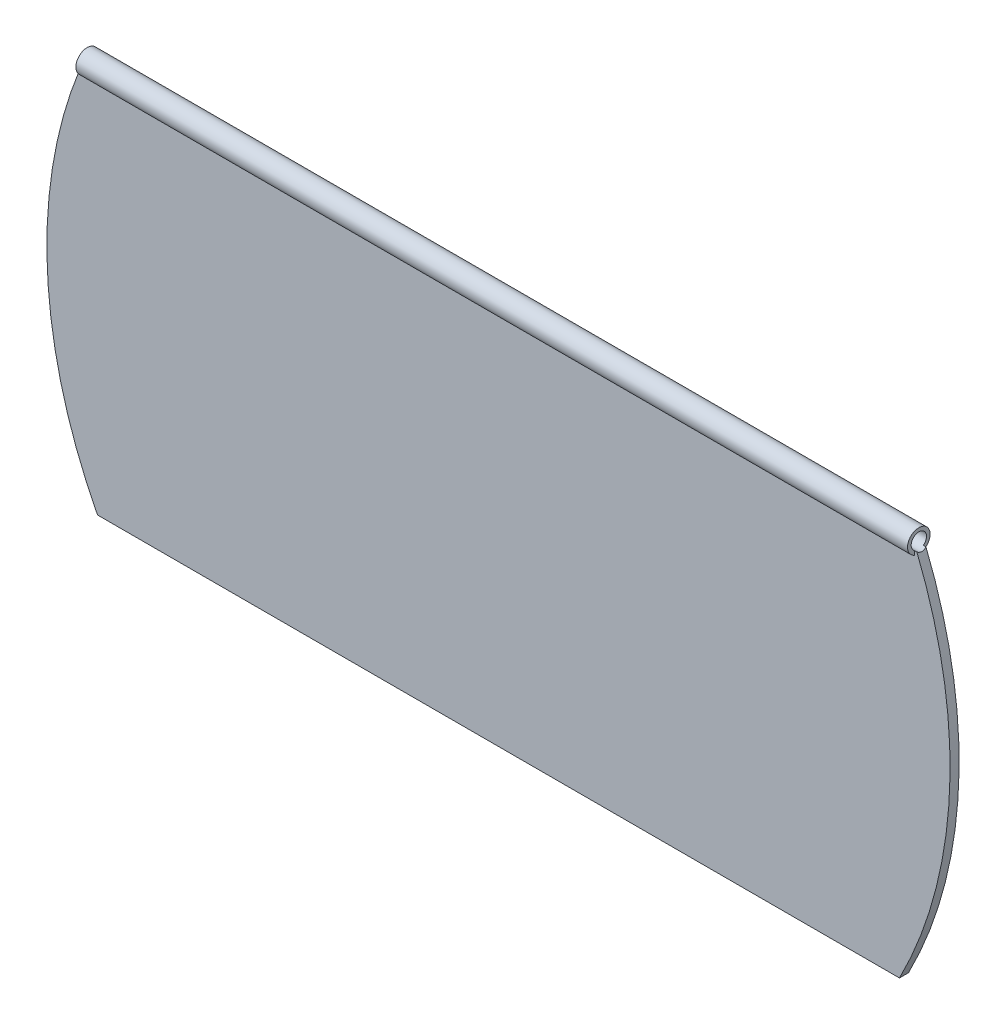
SolidWorks part; units mm, degrees
ref_plane "前视基准面" through (0, 0, 0) normal (0, 0, 1) x (1, 0, 0)
ref_plane "上视基准面" through (0, 0, 0) normal (0, 1, 0) x (1, 0, 0)
ref_plane "右视基准面" through (0, 0, 0) normal (1, 0, 0) x (0, 0, -1)
sketch "草图1" plane through (0, 0, 0) normal (0, 0, 1) x (1, 0, 0)
  arc A0 (-203, 0) -> (203, 0) centre (0, 0) ccw
  arc A1 (-210, 0) -> (210, 0) centre (0, 0) ccw
  arc A2 (-203, 0) -> (203, 0) centre (0, 0) ccw
  circle A3 centre (0, 0) radius 210
  circle A4 centre (0, 0) radius 203
  point P12 (0, 0)
extrude "凸台-拉伸2" add sketch "草图1" along normal blind 174
sketch "草图2" plane through (0, 0, 174) normal (0, 0, 1) x (1, 0, 0)
  line L0 (-173.7354, -102) -> (-170.7354, -102)
  line L1 (-170.7354, -102) -> (-170.7354, -105)
  line L2 (-170.7354, -105) -> (-173.7354, -105)
  line L3 (173.7354, -102) -> (170.7354, -102)
  line L4 (-173.7354, -102) -> (-175.5135, -102)
  line L6 (173.7354, -102) -> (175.5135, -102)
  line L7 (173.7354, -105) -> (170.7354, -105)
  line L8 (170.7354, -105) -> (170.7354, -102)
  circle A0 centre (0, 0) radius 203 construction
  arc A1 (0, -203) -> (-173.7354, -105) centre (0, 0) ccw
  circle M4 centre (0, 0) radius 203
extrude "凸台-拉伸4" add sketch "草图2" against normal up to surface (174 mm away) contours L0 L4 L2 L1 M4 | L8 L7 L6 L3 M4 up to face at (203, 0, 0)
sketch "草图3" plane through (0, 0, 174) normal (0, 0, 1) x (1, 0, 0)
  line L0 (-170.7354, -102) -> (238.3336, -102)
  line L1 (238.3336, -102) -> (254.3342, 272.2925)
  line L2 (254.3342, 272.2925) -> (-334.5694, 221.8511)
  line L3 (-170.7354, -102) -> (-306.8306, -102)
  line L4 (-306.8306, -102) -> (-334.5694, 221.8511)
extrude "切除-拉伸1" cut sketch "草图3" against normal blind 654
ref_plane "基准面1" through (0, -209.75, 0) normal (0, 1, 0) x (1, 0, 0)
sketch "草图5" plane through (0, 0, 174) normal (0, 0, 1) x (1, 0, 0)
  line L0 (0, -209.75) -> (120, -209.75)
  line L1 (95.7, -209.75) -> (-95.7, -209.75) construction
  line L2 (120, -209.75) -> (120, -172.0322)
  line L3 (0, -209.75) -> (-120, -209.75)
  line L4 (-120, -209.75) -> (-120, -172.0322)
  arc A0 (-120, -172.0322) -> (120, -172.0322) centre (0, 0) ccw
  arc M3 (-183.5647, -102) -> (183.5647, -102) centre (0, 0) ccw
extrude "凸台-拉伸5" add sketch "草图5" against normal up to surface (174 mm away) contours L4 L3 M3 | L0 L2 M3 up to face at (0, -129.25, 0)
sketch "草图6" plane through (0, 0, 174) normal (0, 0, 1) x (1, 0, 0)
  line L0 (-175.5135, -102) -> (-166.1957, -102)
  line L1 (175.5135, -102) -> (166.1957, -102)
  arc A0 (-166.1957, -102) -> (166.1957, -102) centre (0, 0) ccw
  arc A1 (-175.5135, -102) -> (175.5135, -102) centre (0, 0) ccw
extrude "凸台-拉伸6" add sketch "草图6" against normal up to surface (174 mm away) up to face at (0, -151.228, 0)
sketch "草图7" plane through (0, 0, 174) normal (0, 0, 1) x (1, 0, 0)
  line L0 (-166.9331, -92) -> (-166.9331, -95)
  line L1 (171.9331, -92) -> (166.9331, -92)
  line L2 (-171.9331, -92) -> (-166.9331, -92)
  line L3 (-188.4969, -92) -> (-171.9331, -92)
  line L4 (171.9331, -92) -> (188.4969, -92)
  line L5 (-166.9331, -95) -> (-170.2939, -95)
  line L6 (166.9331, -92) -> (166.9331, -95)
  line L7 (166.9331, -95) -> (170.2939, -95)
  arc A1 (-188.4969, -92) -> (188.4969, -92) centre (0, 0) ccw
  arc A2 (-170.2939, -95) -> (170.2939, -95) centre (0, 0) ccw
extrude "凸台-拉伸7" add sketch "草图7" against normal up to surface (174 mm away) up to face at (0, -169.2192, 0)
sketch "草图8" plane through (0, 0, 0) normal (0, 0, -1) x (-1, 0, 0)
  line L0 (166.9331, -92) -> (163.9331, -92)
  line L1 (163.9331, -92) -> (163.9331, -99)
  line L2 (163.9331, -99) -> (168, -99)
  line L3 (166.9331, -92) -> (166.9331, -95)
  line L4 (166.9331, -95) -> (170.2939, -95)
  line L6 (-166.9331, -95) -> (-170.2939, -95)
  line L7 (-166.9331, -92) -> (-166.9331, -95)
  line L8 (-163.9331, -99) -> (-168, -99)
  line L9 (-163.9331, -92) -> (-163.9331, -99)
  line L10 (-166.9331, -92) -> (-163.9331, -92)
  arc A0 (-170.2939, -95) -> (170.2939, -95) centre (0, 0) ccw construction
  arc A1 (168, -99) -> (170.2939, -95) centre (0, 0) ccw
  arc A2 (-168, -99) -> (-170.2939, -95) centre (0, 0) cw
extrude "凸台-拉伸8" add sketch "草图8" against normal up to surface (174 mm away) up to face at (0, -135.959, 174)
sketch "草图9" plane through (0, 0, 174) normal (0, 0, 1) x (1, 0, 0)
  line L0 (0, 0) -> (0, -337.2155)
  line L3 (-50, -195) -> (-50, -209.75)
  line L4 (-10.2439, -209.75) -> (-120, -209.75) construction
  line L5 (-50, -209.75) -> (50, -209.75)
  line L6 (10.2439, -209.75) -> (120, -209.75) construction
  line L7 (50, -209.75) -> (50, -195)
  line L8 (-50, -195) -> (-50, -182.2253)
  line L9 (-50, -182.2253) -> (50, -182.2253)
  line L10 (50, -182.2253) -> (50, -195)
  arc M4 (168, -99) -> (-168, -99) centre (0, 0) cw
  line M12 (-120, -209.75) -> (-10.2439, -209.75)
  line M14 (10.2439, -209.75) -> (120, -209.75)
extrude "切除-拉伸2" cut sketch "草图9" against normal blind 654 contours L9 L8 L0 M4 | L8 L3 L5 L0 M12 M4 | L10 L0 L5 L7 M4 M14 | L10 L9 L0 M4
sketch "草图10" plane through (0, -209.75, 0) normal (0, 1, 0) x (1, 0, 0)
  line L1 (-10.2439, 0) -> (10.2439, 0)
  line L2 (-10.2439, 0) -> (-10.2439, -174)
  line L3 (-10.2439, -174) -> (10.2439, -174)
  line L4 (10.2439, 0) -> (10.2439, -174)
extrude "切除-拉伸3" cut sketch "草图10" against normal mid plane 654
sketch "草图11" plane through (0, 0, 0) normal (0, 0, -1) x (-1, 0, 0)
  line L1 (18.7676, -16.6345) -> (254.4053, -16.6345)
  line L2 (18.7676, -16.6345) -> (18.7676, -265.8266)
  line L3 (18.7676, -265.8266) -> (254.4053, -265.8266)
  line L4 (254.4053, -16.6345) -> (254.4053, -265.8266)
extrude "切除-拉伸4" cut sketch "草图11" against normal blind 238
ref_plane "基准面2" through (0, 0, 209.75) normal (0, 0, 1) x (1, 0, 0)
sketch "草图14" plane through (0, 0, 209.75) normal (0, 0, 1) x (1, 0, 0)
  line L0 (188.4969, -92) -> (183.1966, -92)
  line L1 (0, 210) -> (0, 205)
  line L2 (183.1966, -92) -> (188.775, -92)
  arc A0 (183.1966, -92) -> (0, 205) centre (0, 0) ccw
  arc A1 (188.775, -92) -> (0, 210) centre (0, 0) ccw
extrude "凸台-拉伸10" add sketch "草图14" along normal blind 174 separate body contours A0 L1 A1 L2
sketch "草图17" plane through (0, -92, 0) normal (0, 1, 0) x (1, 0, 0)
  line L1 (-19.1853, 5.1617) -> (266.9134, 5.1617)
  line L2 (-19.1853, 5.1617) -> (-19.1853, -186.717)
  line L3 (-19.1853, -186.717) -> (266.9134, -186.717)
  line L4 (266.9134, 5.1617) -> (266.9134, -186.717)
extrude "切除-拉伸5" cut sketch "草图17" against normal blind 322
sketch "草图18" plane through (0, 0, 383.75) normal (0, 0, 1) x (1, 0, 0)
  line L0 (0, 210) -> (0, 205)
  line L1 (188.775, -92) -> (183.1966, -92)
  line L2 (-183.1966, -92) -> (-188.775, -92)
  arc A0 (0, 205) -> (-183.1966, -92) centre (0, 0) ccw
  arc A1 (0, 210) -> (-188.775, -92) centre (0, 0) ccw
  line M3 (0, 210) -> (0, 205)
extrude "凸台-拉伸11" add sketch "草图18" against normal up to surface (174 mm away) contours A1 L2 A0 M3 up to face at (134.6342, 83.6081, 209.75)
sketch "草图21" plane through (0, 0, 0) normal (0, 0, 1) x (1, 0, 0)
  line L1 (177.5838, -92) -> (-177.5838, -92)
  line L3 (184.163, 78) -> (-184.163, 78)
  arc A0 (177.5838, -92) -> (184.163, 78) centre (0, 0) ccw
  arc A1 (-184.163, 78) -> (-177.5838, -92) centre (0, 0) ccw
  point P11 (0, 78)
extrude "凸台-拉伸13" add sketch "草图21" along normal blind 4 separate body
sketch "草图27" plane through (0, 0, 0) normal (0, 1, 0) x (1, 0, 0)
  line L1 (-304.3, -179.7549) -> (279.8723, -179.7549)
  line L2 (-304.3, -179.7549) -> (-304.3, -402.3965)
  line L3 (-304.3, -402.3965) -> (279.8723, -402.3965)
  line L4 (279.8723, -179.7549) -> (279.8723, -402.3965)
extrude "切除-拉伸7" cut sketch "草图27" against normal mid plane 500
sketch "草图31" plane through (0, 0, 0) normal (1, 0, 0) x (0, 0, -1)
  line L0 (-4, 78) -> (0, 78) construction
  circle A0 centre (-2, 78) radius 5
  circle A1 centre (-2, 78) radius 3.4
extrude "凸台-拉伸14" add sketch "草图31" along normal up to vertex (184.163 mm away) up to point (184.163, 78, 4)
sketch "草图32" plane through (0, 0, 0) normal (-1, 0, 0) x (0, 0, 1)
  line L0 (4, 78) -> (0, 78) construction
  circle A0 centre (2, 78) radius 5
extrude "凸台-拉伸15" add sketch "草图32" along normal up to vertex (184.163 mm away) up to point (-184.163, 78, 0)
sketch "草图33" plane through (184.163, 0, 0) normal (1, 0, 0) x (0, 0, -1)
  line L0 (-4, 78) -> (0, 78) construction
  circle A0 centre (-2, 78) radius 3.4
extrude "切除-拉伸8" cut sketch "草图33" against normal up to next
sketch "草图34" plane through (184.163, 0, 0) normal (1, 0, 0) x (0, 0, -1)
  line L0 (-4, 78) -> (0, 78) construction
  circle A0 centre (-2, 78) radius 3.4
extrude "切除-拉伸9" cut sketch "草图34" along normal blind 10
